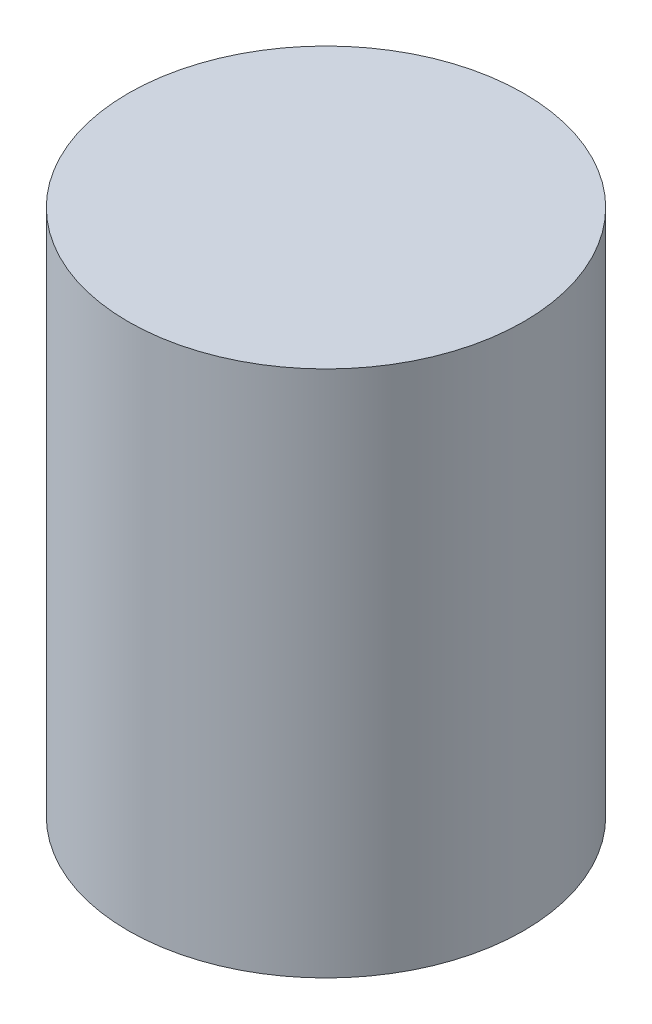
SolidWorks part; units mm, degrees
ref_plane "前基準面" through (0, 0, 0) normal (0, 0, 1) x (1, 0, 0)
ref_plane "上基準面" through (0, 0, 0) normal (0, 1, 0) x (1, 0, 0)
ref_plane "右基準面" through (0, 0, 0) normal (1, 0, 0) x (0, 0, -1)
sketch "草圖1" plane through (0, 0, 0) normal (0, 1, 0) x (1, 0, 0)
  circle A0 centre (0, 0) radius 30
extrude "填料-伸長1" add sketch "草圖1" along normal blind 80
